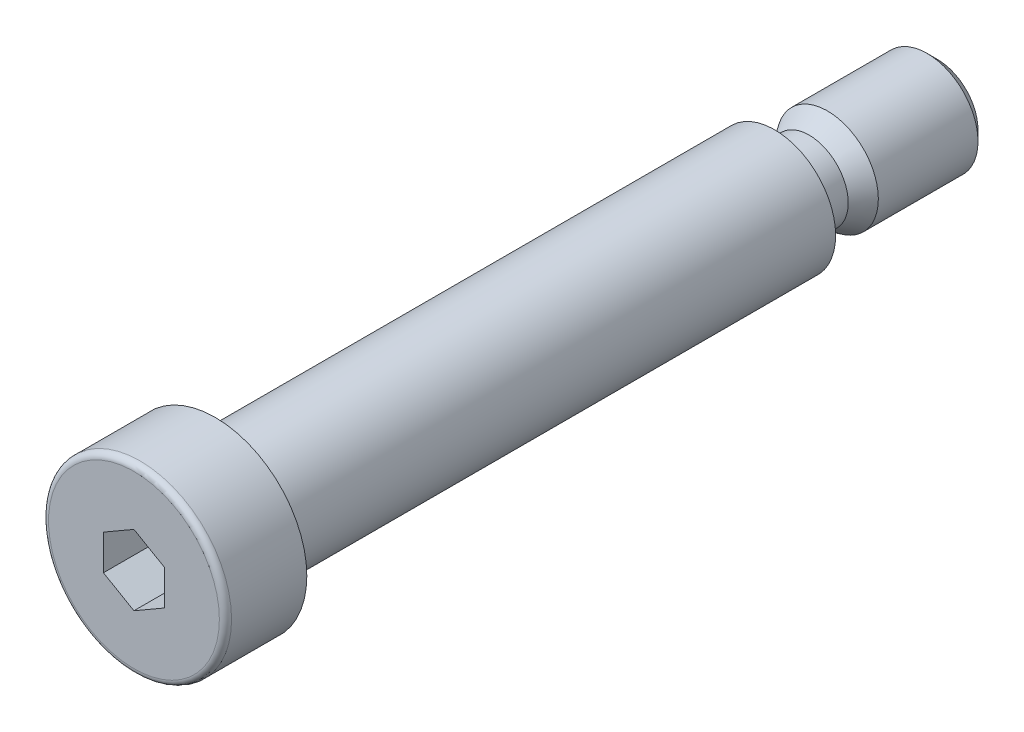
SolidWorks part; units mm, degrees
material "1.0545 (S355N)"
ref_plane "Płaszczyzna przednia" through (0, 0, 0) normal (0, 0, 1) x (1, 0, 0)
ref_plane "Płaszczyzna górna" through (0, 0, 0) normal (0, 1, 0) x (1, 0, 0)
ref_plane "Płaszczyzna prawa" through (0, 0, 0) normal (1, 0, 0) x (0, 0, -1)
sketch "Szkic1" plane through (0, 0, 0) normal (0, 1, 0) x (1, 0, 0)
  line L0 (5, 32.7) -> (3.85, 30.89)
  line L1 (9, -35.5) -> (-9, -35.5)
  line L2 (9, -35.5) -> (9, -27.5)
  line L3 (9, -27.5) -> (-9, -27.5)
  line L4 (-9, -35.5) -> (-9, -27.5)
  line L5 (6, -27.5) -> (-6, -27.5)
  line L6 (6, -27.5) -> (6, 27.5)
  line L7 (6, 27.5) -> (-6, 27.5)
  line L8 (-6, -27.5) -> (-6, 27.5)
  line L9 (-3.85, 27.5) -> (3.85, 27.5)
  line L10 (-3.85, 27.5) -> (-3.85, 30.89)
  line L11 (-3.85, 30.89) -> (3.85, 30.89)
  line L12 (3.85, 27.5) -> (3.85, 30.89)
  line L13 (5, 32.7) -> (5, 42.5)
  line L14 (5, 42.5) -> (4, 43.5)
  line L15 (4, 43.5) -> (-4, 43.5)
  line L16 (-4, 43.5) -> (-5, 42.5)
  line L17 (-5, 42.5) -> (-5, 32.7)
  line L18 (-5, 32.7) -> (-3.85, 30.89)
  line L19 (5, 32.7) -> (-5, 32.7) construction
  line L20 (5, 42.5) -> (-5, 42.5) construction
  line L21 (0, -19.9356) -> (0, 25.6583) construction
  line L22 (0, -35.5) -> (0, 43.5)
  point P4 (0, -27.5)
  point P14 (0, -27.5)
  point P15 (0, 27.5)
  point P16 (0, 27.5)
  point P17 (-6, 0)
  point P23 (0, 32.7)
  point P25 (0, 43.5)
  point P26 (0, 30.89)
  point P27 (0, 42.5)
  dimension "D1" = 18
  dimension "D2" = 8
  dimension "D3" = 12
  dimension "l1" = 55
  dimension "D5" = 7.7
  dimension "D6" = 16
  dimension "D7" = 10
  dimension "D8" = 8
  dimension "D9" = 1
  dimension "D10" = 1.81
  dimension "D11" = 9.8
revolve "Obrót1" add sketch "Szkic1" angle 360 about L22
sketch "Szkic2" plane through (0, 0, 35.5) normal (0, 0, 1) x (1, 0, 0)
  line L1 (3, 1.7321) -> (0, 3.4641)
  line L2 (0, 3.4641) -> (-3, 1.7321)
  line L3 (-3, 1.7321) -> (-3, -1.7321)
  line L4 (-3, -1.7321) -> (0, -3.4641)
  line L5 (0, -3.4641) -> (3, -1.7321)
  line L6 (3, -1.7321) -> (3, 1.7321)
  circle A0 centre (0, 0) radius 3 construction
  dimension "D1" = 6
extrude "Wytnij-wyciągnięcie1" cut sketch "Szkic2" against normal blind 4.9
fillet "Zaokrąglenie1" radius 0.6 1 edges at (9, 0, 35.5)
